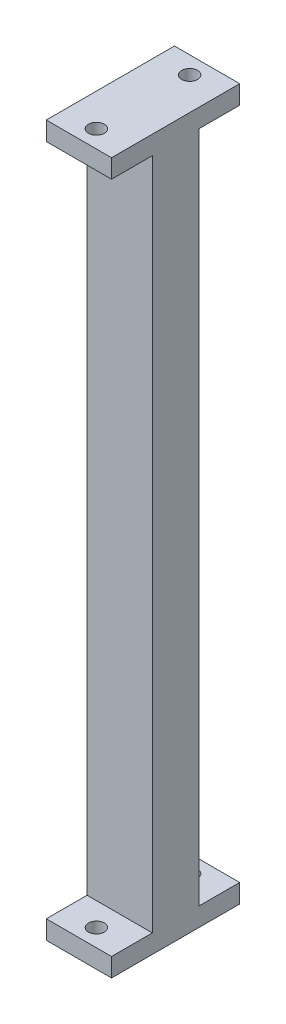
SolidWorks part; units mm, degrees
ref_plane "Front Plane" through (0, 0, 0) normal (0, 0, 1) x (1, 0, 0)
ref_plane "Top Plane" through (0, 0, 0) normal (0, 1, 0) x (1, 0, 0)
ref_plane "Right Plane" through (0, 0, 0) normal (1, 0, 0) x (0, 0, -1)
sketch "Sketch1" plane through (0, 0, 0) normal (0, 1, 0) x (1, 0, 0)
  line L1 (-7, 5) -> (7, 5)
  line L2 (-7, 5) -> (-7, -5)
  line L3 (-7, -5) -> (7, -5)
  line L4 (7, 5) -> (7, -5)
  line L5 (-7, 5) -> (7, -5) construction
  line L6 (-7, -5) -> (7, 5) construction
  point P0 (0, 0)
  dimension "D1" = 10
  dimension "D2" = 14
extrude "Boss-Extrude1" add sketch "Sketch1" along normal mid plane 152.4
sketch "Sketch3" plane through (0, 76.2, 0) normal (0, 1, 0) x (1, 0, 0)
  line L0 (0, 13.75) -> (0, -13.75) construction
  line L1 (7, 13.75) -> (-7, 13.75)
  line L16 (7, -5) -> (7, 5) construction
  line L17 (7, 13.75) -> (7, -13.75)
  line L18 (7, -13.75) -> (-7, -13.75)
  line L19 (-7, 13.75) -> (-7, -13.75)
  line L20 (-7, 5) -> (-7, -5) construction
  line L21 (-7, 0) -> (7, 0) construction
  circle A6 centre (0, 10) radius 1.7
  circle A7 centre (0, -10) radius 1.7
  dimension "D1" = 27.5
  dimension "D2" = 20
  dimension "D3" = 3.4
extrude "Boss-Extrude3" add sketch "Sketch3" against normal blind 4
mirror "Mirror1" about plane through (0, 0, 0) normal (0, 1, 0) of "Boss-Extrude3"
